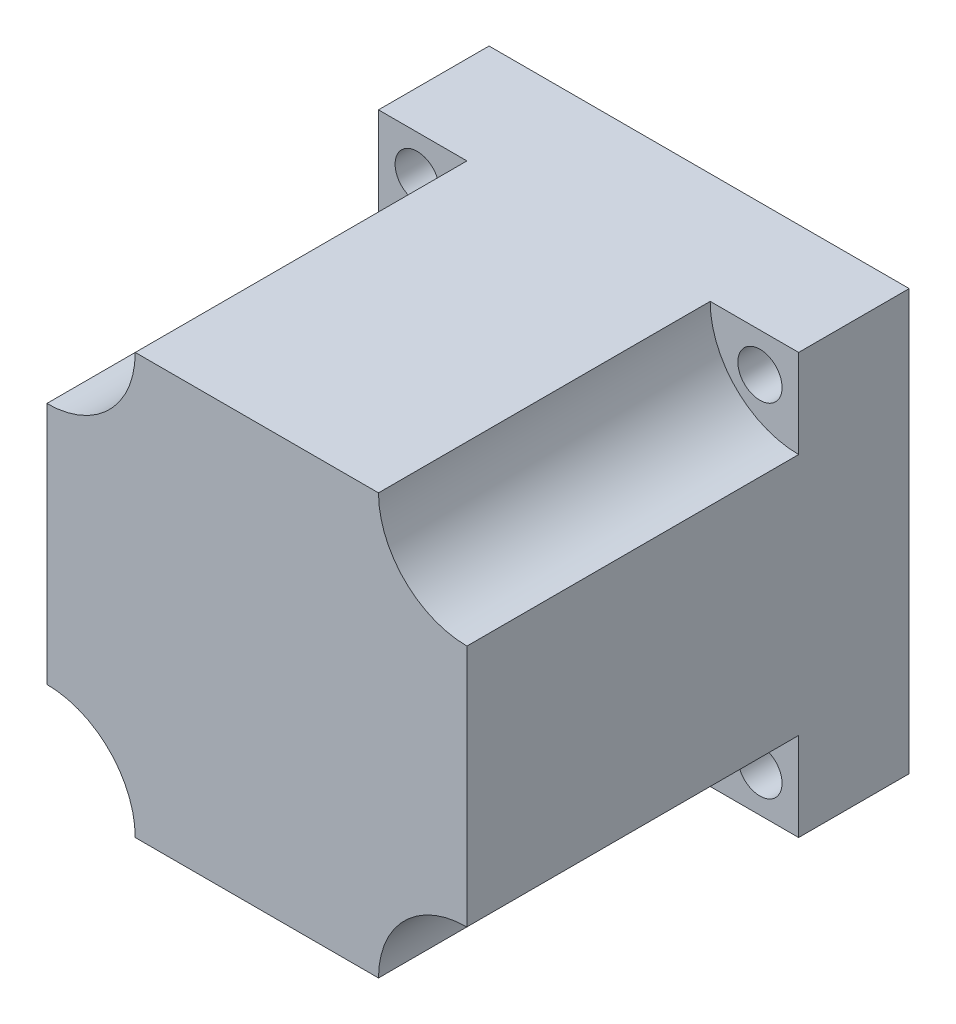
SolidWorks part; units mm, degrees
ref_plane "Front Plane" through (0, 0, 0) normal (0, 0, 1) x (1, 0, 0)
ref_plane "Top Plane" through (0, 0, 0) normal (0, 1, 0) x (1, 0, 0)
ref_plane "Right Plane" through (0, 0, 0) normal (1, 0, 0) x (0, 0, -1)
sketch "Sketch1" plane through (0, 0, 0) normal (0, 0, 1) x (1, 0, 0)
  line L1 (-19, -19) -> (19, -19)
  line L2 (-19, -19) -> (-19, 19)
  line L3 (-19, 19) -> (19, 19)
  line L4 (19, -19) -> (19, 19)
  line L5 (-19, -19) -> (19, 19) construction
  line L6 (-19, 19) -> (19, -19) construction
  point P0 (0, 0)
  dimension "D1" = 38
  dimension "D2" = 38
extrude "Boss-Extrude1" add sketch "Sketch1" along normal blind 10
sketch "Sketch2" plane through (0, 0, 10) normal (0, 0, 1) x (1, 0, 0)
  line L0 (19, -19) -> (19, 19) construction
  line L1 (19, 19) -> (-19, 19) construction
  circle A0 centre (15.5, 15.5) radius 2
  circle A1 centre (15.5, -15.5) radius 2
  circle A2 centre (-15.5, -15.5) radius 2
  circle A3 centre (-15.5, 15.5) radius 2
  dimension "D1" = 4
  dimension "D2" = 4
  dimension "D3" = 4
  dimension "D4" = 4
  dimension "D5" = 31
  dimension "D6" = 31
  dimension "D7" = 31
  dimension "D8" = 3.5
  dimension "D9" = 3.5
extrude "Cut-Extrude1" cut sketch "Sketch2" against normal through all contours A0 | A1 | A2 | A3
sketch "Sketch3" plane through (0, 0, 10) normal (0, 0, 1) x (1, 0, 0)
  circle A0 centre (0, 0) radius 2.5
  dimension "D1" = 5
sketch "Sketch4" plane through (0, 0, 10) normal (0, 0, 1) x (1, 0, 0)
  circle A0 centre (0, 0) radius 2.5
  dimension "D1" = 5
sketch "Sketch5" plane through (0, 0, 10) normal (0, 0, 1) x (1, 0, 0)
  circle A0 centre (0, 0) radius 2.5
  dimension "D1" = 5
sketch "Sketch6" plane through (0, 0, 10) normal (0, 0, 1) x (1, 0, 0)
  line L0 (-19, 19) -> (-19, -19) construction
  line L1 (19, 19) -> (-19, 19) construction
  line L2 (5.5, 0) -> (-5.5, 0) construction
  line L3 (0, -5.5) -> (0, 5.5) construction
  line L4 (-19, 11) -> (-19, -11)
  line L5 (-11, -19) -> (11, -19)
  line L6 (19, -11) -> (19, 11)
  line L7 (11, 19) -> (-11, 19)
  arc A0 (-19, 11) -> (-11, 19) centre (-19, 19) ccw
  arc A1 (-19, -11) -> (-11, -19) centre (-19, -19) cw
  arc A2 (19, -11) -> (11, -19) centre (19, -19) ccw
  arc A3 (19, 11) -> (11, 19) centre (19, 19) cw
extrude "Boss-Extrude2" add sketch "Sketch6" along normal blind 30
sketch "Sketch8" plane through (0, 0, 0) normal (0, 0, -1) x (-1, 0, 0)
  circle A0 centre (0, 0) radius 2.5
  dimension "D1" = 5
extrude "Boss-Extrude4" add sketch "Sketch8" along normal blind 10
